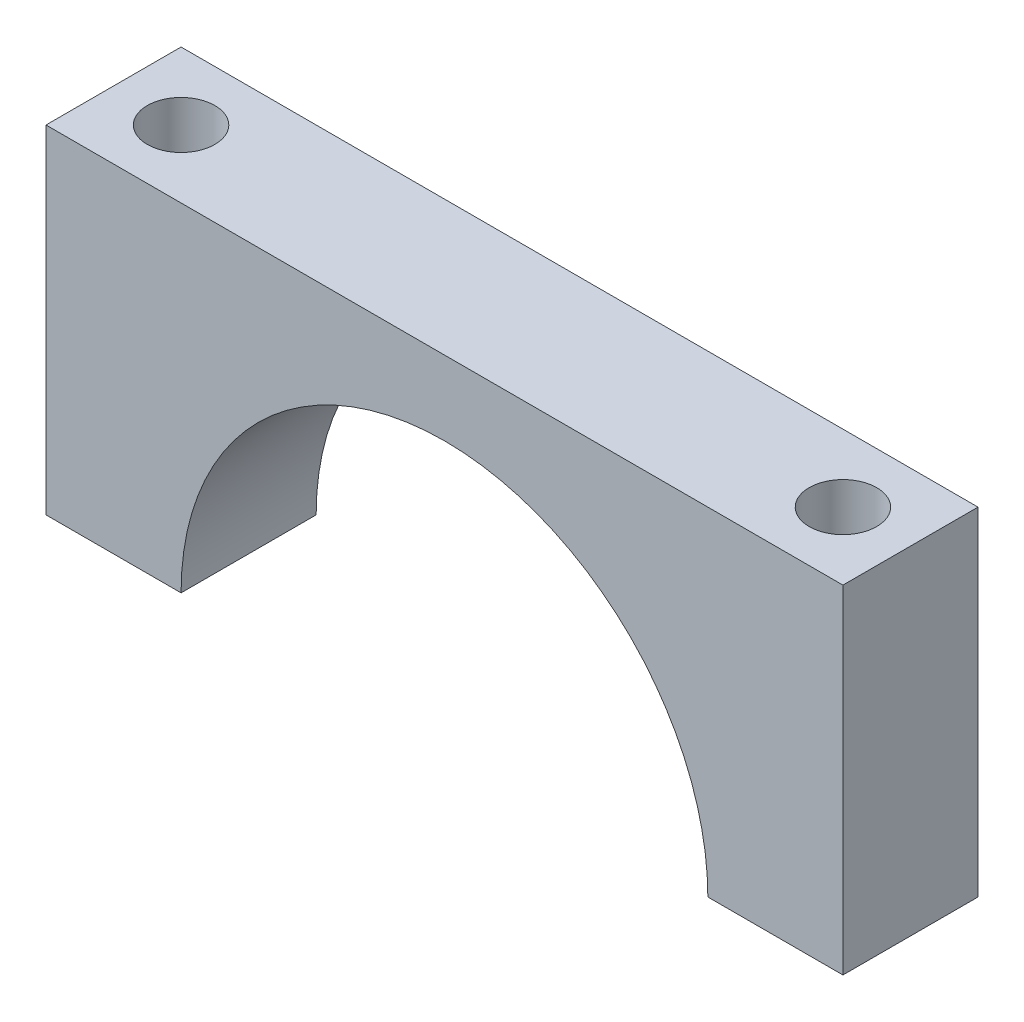
SolidWorks part; units mm, degrees
ref_plane "Front Plane" through (0, 0, 0) normal (0, 0, 1) x (1, 0, 0)
ref_plane "Top Plane" through (0, 0, 0) normal (0, 1, 0) x (1, 0, 0)
ref_plane "Right Plane" through (0, 0, 0) normal (1, 0, 0) x (0, 0, -1)
sketch "Sketch1" plane through (0, 0, 0) normal (0, 0, 1) x (1, 0, 0)
  line L0 (55, 0) -> (-55, 0) construction
  line L1 (-19.5, 0) -> (-29.5, 0)
  line L2 (-29.5, 0) -> (-29.5, 25)
  line L3 (-29.5, 25) -> (29.5, 25)
  line L4 (29.5, 25) -> (29.5, 0)
  line L5 (29.5, 0) -> (19.5, 0)
  arc A0 (-19.5, 0) -> (19.5, 0) centre (0, 0) cw
  dimension "D1" = 19.5
  dimension "D2" = 10
  dimension "D3" = 25
  dimension "D4" = 59
extrude "Boss-Extrude1" add sketch "Sketch1" along normal blind 10
sketch "Sketch2" plane through (0, 0, 0) normal (0, 1, 0) x (1, 0, 0)
  line L0 (29.5, -10) -> (29.5, 0) construction
  line L1 (-29.5, -10) -> (-29.5, 0) construction
  line L2 (-44.2539, 0) -> (44.2539, 0) construction
  circle A0 centre (-24.5, -5) radius 2.5
  circle A1 centre (24.5, -5) radius 2.5
  dimension "D1" = 5
  dimension "D2" = 5
  dimension "D3" = 5
  dimension "D4" = 5
  dimension "D5" = 5
  dimension "D6" = 5
extrude "Cut-Extrude2" cut sketch "Sketch2" along normal through all
